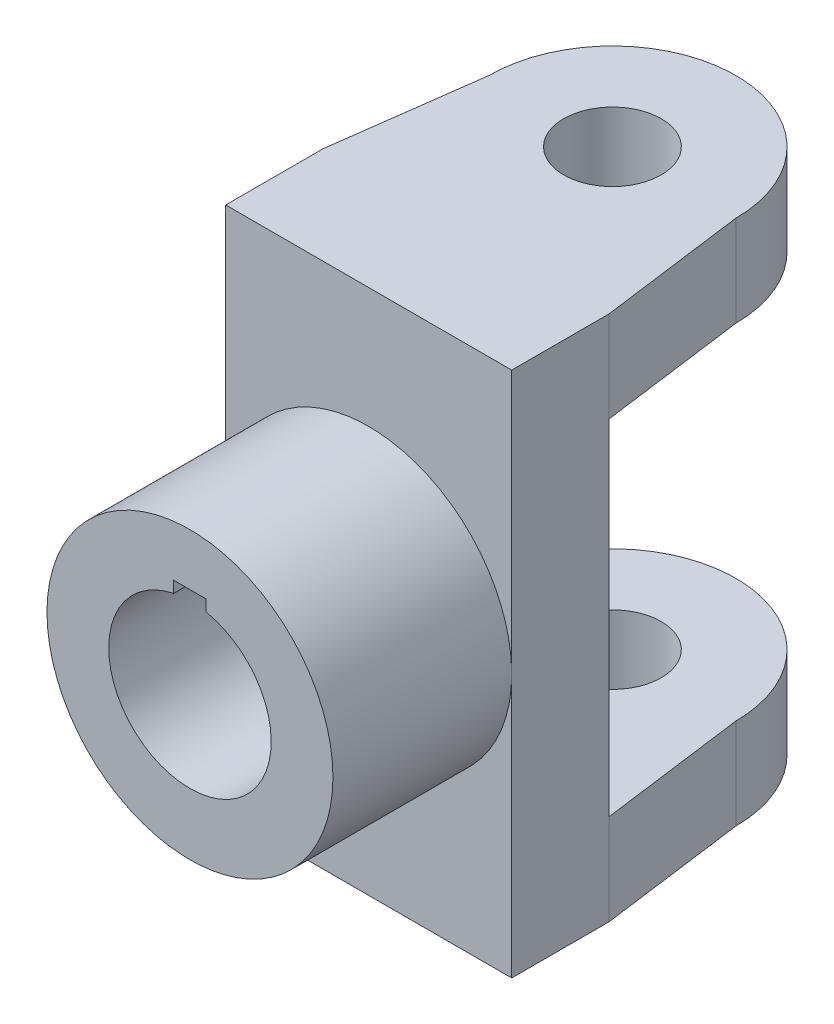
SolidWorks part; units mm, degrees
material "Gray Cast Iron"
ref_plane "Front Plane" through (0, 0, 0) normal (0, 0, 1) x (1, 0, 0)
ref_plane "Top Plane" through (0, 0, 0) normal (0, 1, 0) x (1, 0, 0)
ref_plane "Right Plane" through (0, 0, 0) normal (1, 0, 0) x (0, 0, -1)
sketch "Sketch1" plane through (0, 0, 0) normal (0, 0, 1) x (1, 0, 0)
  line L1 (-44, 81) -> (44, 81)
  line L2 (-44, 81) -> (-44, -81)
  line L3 (-44, -81) -> (44, -81)
  line L4 (44, 81) -> (44, -81)
  line L5 (-44, 81) -> (44, -81) construction
  line L6 (-44, -81) -> (44, 81) construction
  point P0 (0, 0)
  dimension "D1" = 88
  dimension "D2" = 162
extrude "Boss-Extrude1" add sketch "Sketch1" along normal blind 30
sketch "Sketch2" plane through (0, 0, 30) normal (0, 0, 1) x (1, 0, 0)
  line L0 (44, -81) -> (44, 81) construction
  line L1 (-5, 24.4949) -> (-5, 28)
  line L2 (-5, 28) -> (5, 28)
  line L3 (5, 28) -> (5, 24.4949)
  arc A0 (-5, 24.4949) -> (5, 24.4949) centre (0, 0) ccw
  circle A1 centre (0, 0) radius 44
  point P9 (0, 0)
  dimension "D1" = 50
  dimension "D2" = 10
  dimension "D3" = 28
extrude "Boss-Extrude2" add sketch "Sketch2" along normal blind 55
sketch "Sketch3" plane through (0, -81, 0) normal (0, -1, 0) x (1, 0, 0)
  line L0 (25, 85) -> (-25, 85) construction
  line L1 (-44, 0) -> (-38, -45)
  line L2 (-44, 0) -> (44, 0)
  line L3 (44, 0) -> (38, -45)
  arc A0 (-38, -45) -> (38, -45) centre (0, -45) ccw
  circle A1 centre (0, -45) radius 15
  dimension "D1" = 76
  dimension "D2" = 30
  dimension "D3" = 130
extrude "Boss-Extrude3" add sketch "Sketch3" against normal blind 28
mirror "Mirror1" about plane through (0, 0, 0) normal (0, 1, 0) of "Boss-Extrude3"
